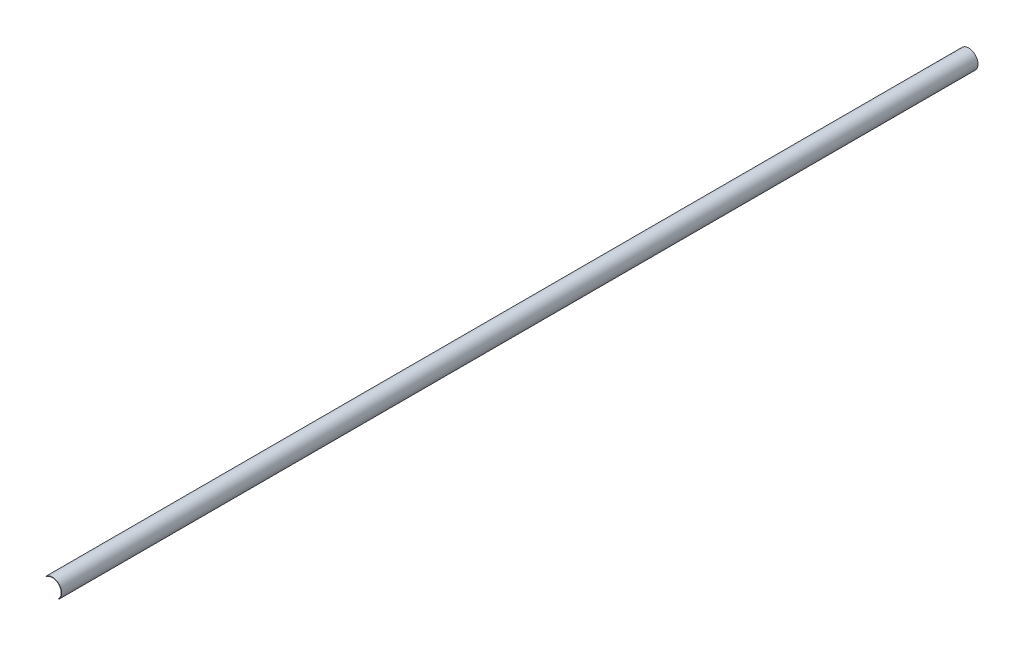
SolidWorks part; units mm, degrees
material "A-Glass Fiber"
ref_plane "Front Plane" through (0, 0, 0) normal (0, 0, 1) x (1, 0, 0)
ref_plane "Top Plane" through (0, 0, 0) normal (0, 1, 0) x (1, 0, 0)
ref_plane "Right Plane" through (0, 0, 0) normal (1, 0, 0) x (0, 0, -1)
sketch "Sketch1" plane through (0, 0, 0) normal (0, 0, 1) x (1, 0, 0)
  line L0 (-13.728, 15.0898) -> (0, 0) construction
  line L1 (0, 0) -> (14.2463, -14.6015) construction
  line L2 (14.9446, -15.3172) -> (14.2463, -14.6015)
  line L4 (-13.728, 15.0898) -> (-14.401, 15.8295)
  arc A0 (-13.728, 15.0898) -> (14.2463, -14.6015) centre (0, 0) cw
  arc A1 (-14.401, 15.8295) -> (14.9446, -15.3172) centre (0, 0) cw
  dimension "D1" = 20.4
  dimension "D3" = 1
  dimension "D2" = 178
  dimension "D4" = 1
extrude "Boss-Extrude1" add sketch "Sketch1" along normal blind 2100
